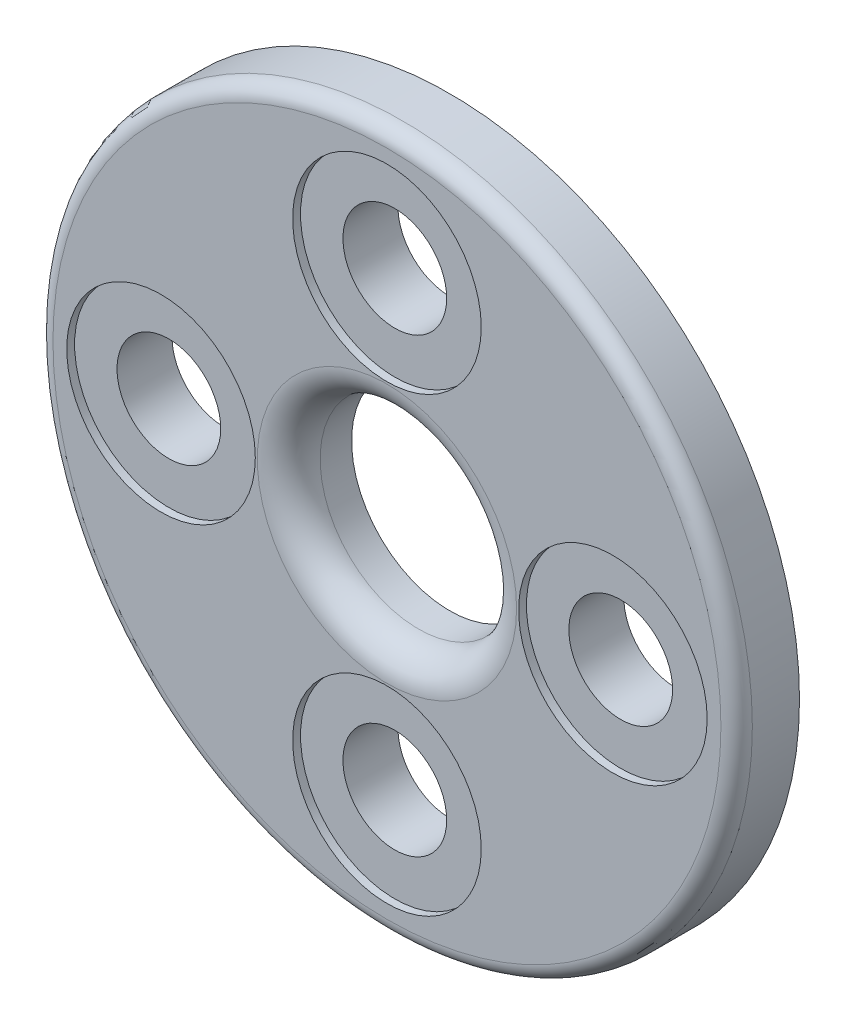
SolidWorks part; units mm, degrees
ref_plane "前视基准面" through (0, 0, 0) normal (0, 0, 1) x (1, 0, 0)
ref_plane "上视基准面" through (0, 0, 0) normal (0, 1, 0) x (1, 0, 0)
ref_plane "右视基准面" through (0, 0, 0) normal (1, 0, 0) x (0, 0, -1)
sketch "草图1" plane through (0, 0, 0) normal (0, 0, 1) x (1, 0, 0)
  circle A0 centre (0, 0) radius 22.25
  circle A1 centre (0, 0) radius 6.25
  dimension "D1" = 12.5
  dimension "D2" = 44.5
extrude "凸台-拉伸1" add sketch "草图1" along normal blind 4
hole_wizard "M6 六角头螺栓的柱形沉头孔1" positions "草图2" profile "草图3" counterbore size "M6" standard "GB" end condition through all
sketch "草图2" plane through (0, 0, 4) normal (0, 0, 1) x (1, 0, 0)
  line L0 (0, 14.375) -> (0, 0) construction
  line L1 (0, 0) -> (14.375, 0) construction
  line L3 (0, -14.375) -> (0, 0) construction
  line L4 (0, 0) -> (-14.375, 0) construction
  circle A0 centre (0, 0) radius 14.375 construction
  point P7 (0, 14.375)
  point P9 (14.375, 0)
  point P11 (0, -14.375)
  point P13 (-14.375, 0)
  dimension "D1" = 28.75
sketch "草图3" plane through (-14.375, 0, 4) normal (1, 0, 0) x (0, -1, 0)
  line L0 (0, 0) -> (0, 4)
  line L1 (0, 4) -> (3.3, 4)
  line L3 (3.3, 4) -> (3.3, 0.5)
  line L4 (3.3, 0.5) -> (6, 0.5)
  line L5 (6, 0.5) -> (6, 0)
  line L7 (6, 0) -> (0, 0)
  line L11 (0, -6.35) -> (0, 107.95) construction
  dimension "通孔孔直径" = 6.6
  dimension "通孔孔深度" = 4
  dimension "柱形沉头孔直径" = 12
  dimension "柱形沉头孔深度" = 0.5
fillet "圆角1" radius 1 1 edges at (22.25, 0, 4)
fillet "圆角2" radius 2 1 edges at (6.25, 0, 4)
